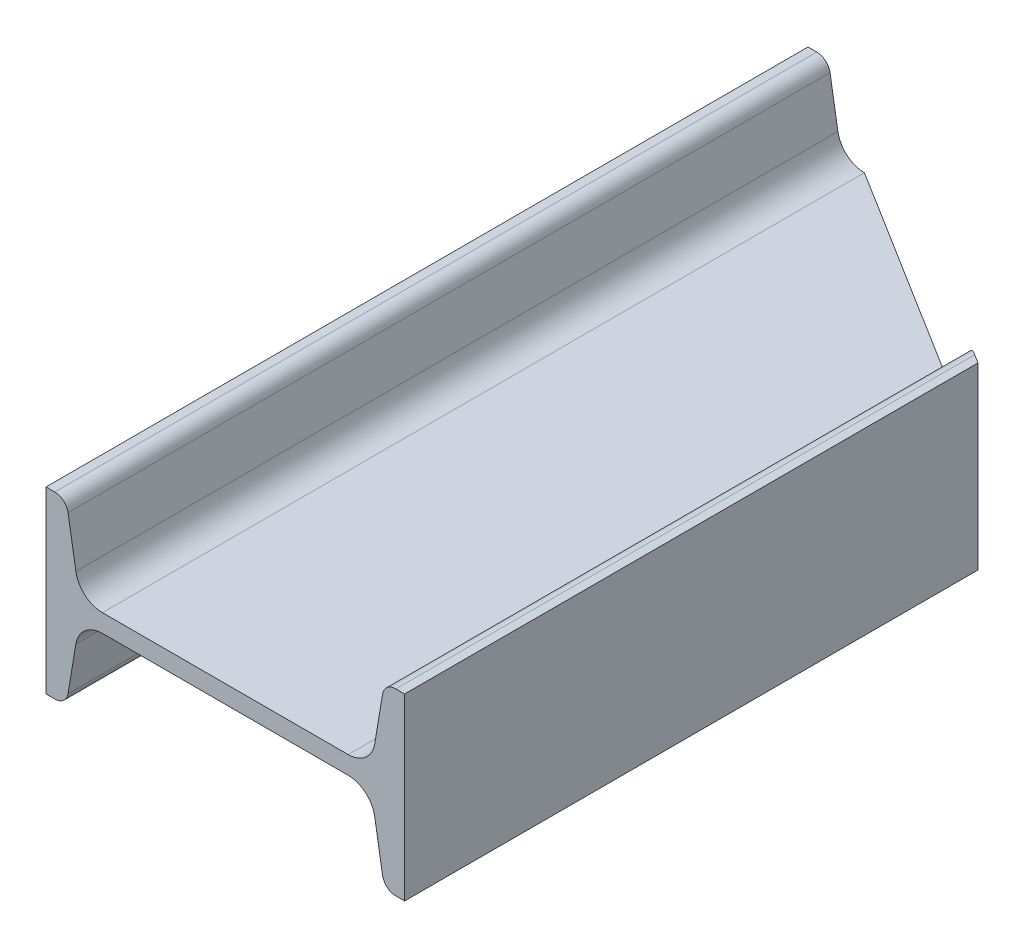
SolidWorks part; units mm, degrees
material "Acero al carbono no aleado"
ref_plane "Alzado" through (0, 0, 0) normal (0, 0, 1) x (1, 0, 0)
ref_plane "Planta" through (0, 0, 0) normal (0, 1, 0) x (1, 0, 0)
ref_plane "Vista lateral" through (0, 0, 0) normal (1, 0, 0) x (0, 0, -1)
sketch "Croquis1" plane through (0, 0, 0) normal (1, 0, 0) x (0, 0, -1)
  line L0 (-85, 0) -> (85, 0)
  point P4 (0, 0)
  dimension "D1" = 170
other "Viga sb 80 X 6(1)"
ref_plane "Plano1" through (0, 0, 85) normal (0, 0, -1) x (0, 1, 0)
sketch "Sketch1" plane through (0, 0, 85) normal (0, 0, -1) x (0, 1, 0)
  line L0 (-20, -40) -> (-20, -38.0415)
  line L1 (-17.4932, -35.0823) -> (-7.0135, -33.3355)
  line L2 (-2, -27.4172) -> (-2, 27.4172)
  line L3 (-7.0135, 33.3355) -> (-17.4932, 35.0823)
  line L4 (-20, 38.0415) -> (-20, 40)
  line L5 (-20, 40) -> (20, 40)
  line L6 (20, 40) -> (20, 38.0415)
  line L7 (17.4932, 35.0823) -> (7.0135, 33.3355)
  line L8 (2, 27.4172) -> (2, -27.4172)
  line L9 (7.0135, -33.3355) -> (17.4932, -35.0823)
  line L10 (20, -38.0415) -> (20, -40)
  line L11 (20, -40) -> (-20, -40)
  line L15 (-2, 0) -> (2, 0) construction
  arc A0 (-7.0135, -33.3355) -> (-2, -27.4172) centre (-8, -27.4172) ccw
  arc A1 (-2, 27.4172) -> (-7.0135, 33.3355) centre (-8, 27.4172) ccw
  arc A2 (7.0135, 33.3355) -> (2, 27.4172) centre (8, 27.4172) ccw
  arc A3 (2, -27.4172) -> (7.0135, -33.3355) centre (8, -27.4172) ccw
  arc A4 (-17.4932, 35.0823) -> (-20, 38.0415) centre (-17, 38.0415) cw
  arc A5 (17.4932, 35.0823) -> (20, 38.0415) centre (17, 38.0415) ccw
  arc A6 (-20, -38.0415) -> (-17.4932, -35.0823) centre (-17, -38.0415) cw
  arc A7 (20, -38.0415) -> (17.4932, -35.0823) centre (17, -38.0415) ccw
  point P1 (0, 40)
  point P8 (0, -40)
  point P21 (0, 0)
  point P34 (0, 0)
  dimension "RI" = 6
  dimension "D3" = 3
  dimension "BF" = 40
  dimension "D2" = 9.463
  dimension "DEPTH" = 80
  dimension "TW" = 4
  dimension "D1" = 54.8344
sketch "Croquis3" plane through (0, 0, 0) normal (0, 1, 0) x (1, 0, 0)
  line L0 (-27.4172, 85) -> (71.2712, 23.4045)
  line L1 (71.2712, 23.4045) -> (71.2712, 105.7624)
  line L2 (71.2712, 105.7624) -> (-27.4172, 105.7624)
  line L3 (-27.4172, 105.7624) -> (-27.4172, 85)
extrude "Cortar-Extruir1" cut sketch "Croquis3" against normal through all both and the other way through all
